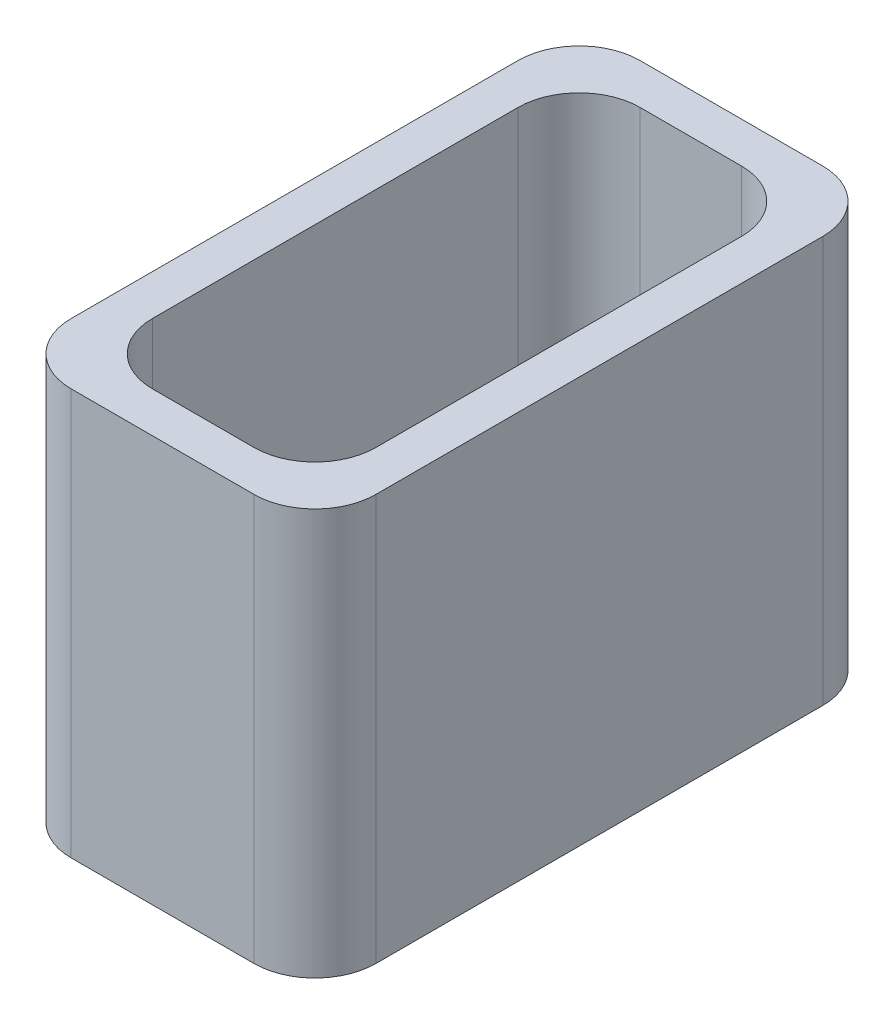
SolidWorks part; units mm, degrees
ref_plane "Alzado" through (0, 0, 0) normal (0, 0, 1) x (1, 0, 0)
ref_plane "Planta" through (0, 0, 0) normal (0, 1, 0) x (1, 0, 0)
ref_plane "Vista lateral" through (0, 0, 0) normal (1, 0, 0) x (0, 0, -1)
sketch "Croquis1" plane through (0, 0, 0) normal (0, 1, 0) x (1, 0, 0)
  line L0 (-6.5, 1) -> (-6.5, -13)
  line L1 (0, 0) -> (-5.5, 0)
  line L2 (0, 0) -> (0, -12)
  line L3 (0, -12) -> (-5.5, -12)
  line L4 (-5.5, 0) -> (-5.5, -12)
  line L5 (1, -13) -> (-6.5, -13)
  line L6 (1, 1) -> (1, -13)
  line L7 (1, 1) -> (-6.5, 1)
  dimension "D1" = 12
  dimension "D2" = 5.5
  dimension "D3" = 1
extrude "Saliente-Extruir1" add sketch "Croquis1" along normal blind 10
fillet "Redondeo1" radius 1.5 8 edges at (-6.5, 5, -1) (1, 5, -1) (1, 5, 13) (-6.5, 5, 13) (0, 5, 0) (-5.5, 5, 0) (0, 5, 12) (-5.5, 5, 12)
